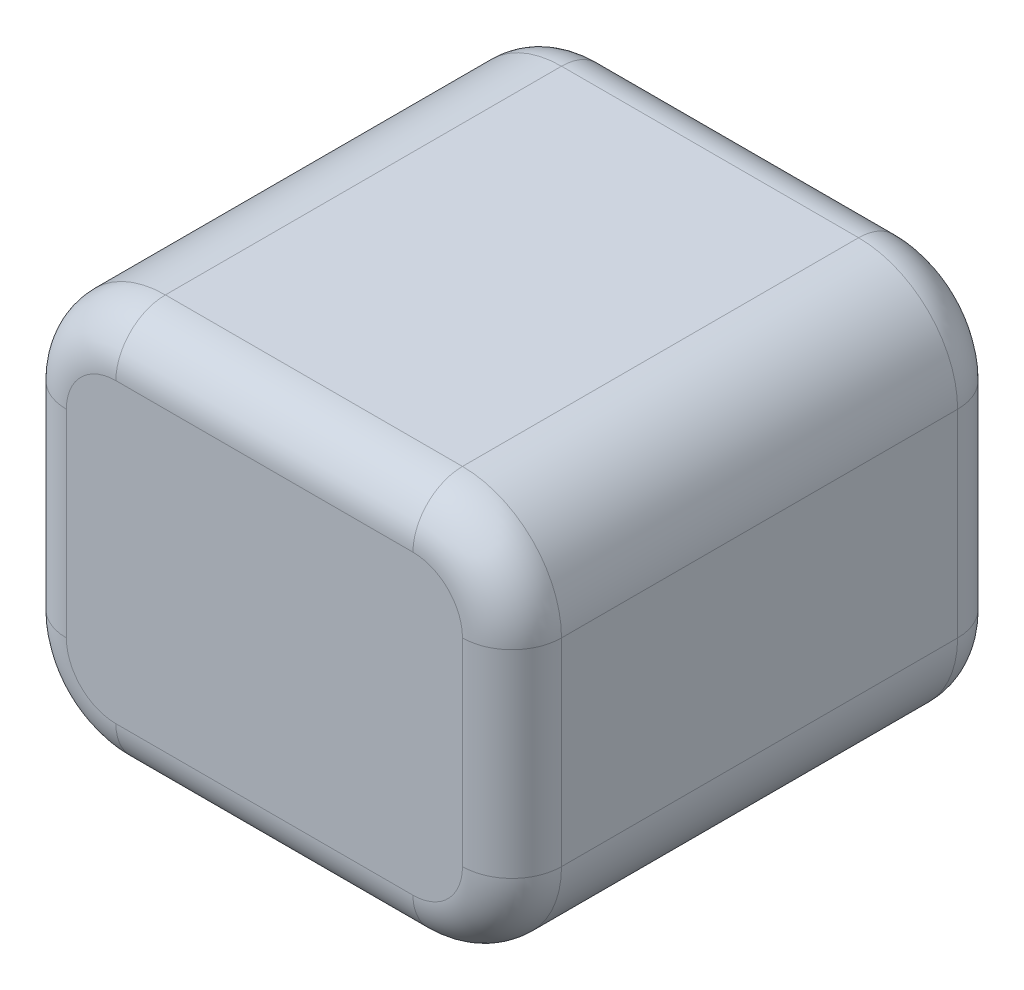
SolidWorks part; units mm, degrees
ref_plane "Спереди" through (0, 0, 0) normal (0, 0, 1) x (1, 0, 0)
ref_plane "Сверху" through (0, 0, 0) normal (0, 1, 0) x (1, 0, 0)
ref_plane "Справа" through (0, 0, 0) normal (1, 0, 0) x (0, 0, -1)
sketch "Эскиз1" plane through (0, 0, 0) normal (0, 0, 1) x (1, 0, 0)
  line L1 (100, 80) -> (0, 80)
  line L2 (100, 80) -> (100, 0)
  line L3 (100, 0) -> (0, 0)
  line L4 (0, 80) -> (0, 0)
  point P5 (-99.9027, 0)
  point P6 (81.5244, 0)
  point P7 (100, 0)
  dimension "D1" = 100
  dimension "D2" = 80
extrude "Бобышка-Вытянуть1" add sketch "Эскиз1" along normal blind 100
fillet "Скругление1" radius 20 4 edges at (100, 80, 50) (100, 0, 50) (0, 80, 50) (0, 0, 50)
fillet "Скругление2" radius 10 16 edges at (5.8579, 5.8579, 100) (0, 40, 100) (5.8579, 74.1421, 100) (50, 80, 100) (94.1421, 74.1421, 100) (100, 40, 100) (94.1421, 5.8579, 100) (5.8579, 5.8579, 0) (0, 40, 0) (5.8579, 74.1421, 0) (50, 80, 0) (94.1421, 74.1421, 0) (100, 40, 0) (94.1421, 5.8579, 0) (50, 0, 100) (50, 0, 0)
sketch "Эскиз2" plane through (0, 0, 0) normal (0, -1, 0) x (1, 0, 0)
  line L0 (20, 10) -> (80, 10) construction
  line L1 (20, 10) -> (80, 10)
  ellipse E0 centre (50, 10) end of major axis (50, 80) minor radius 30 (80, 10) -> (20, 10) ccw
  point P1 (50, 74.5925)
  point P2 (0, 0)
  point P7 (0, 0)
  point P12 (0, 0)
  point P13 (0, 0)
  point P14 (0, 0)
  point P15 (0, 0)
  dimension "D1" = 70
  dimension "D2" = 60
extrude "Вырез-Вытянуть1" cut sketch "Эскиз2" against normal blind 5 contours E0 L1
